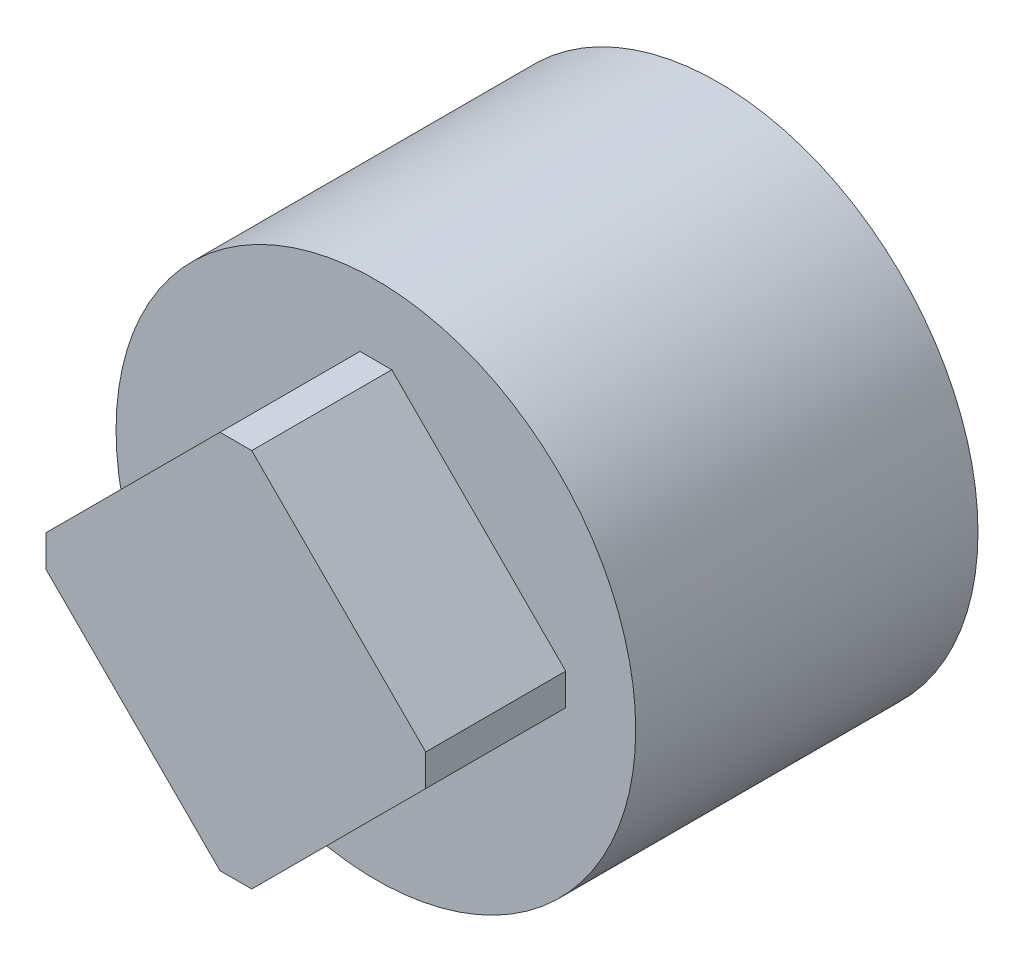
SolidWorks part; units mm, degrees
ref_plane "Front Plane" through (0, 0, 0) normal (0, 0, 1) x (1, 0, 0)
ref_plane "Top Plane" through (0, 0, 0) normal (0, 1, 0) x (1, 0, 0)
ref_plane "Right Plane" through (0, 0, 0) normal (1, 0, 0) x (0, 0, -1)
sketch "Sketch1" plane through (0, 0, 0) normal (0, 0, 1) x (1, 0, 0)
  circle A0 centre (0, 0) radius 16.7
extrude "Replaceable drive insert body" add sketch "Sketch1" along normal blind 22 from offset 1
sketch "Sketch2" plane through (0, 0, 0) normal (0, 0, 1) x (1, 0, 0)
  line L0 (1.02, 12.2029) -> (-1.02, 12.2029)
  line L1 (-1.02, 12.2029) -> (-12.2029, 1.02)
  line L2 (-12.2029, 1.02) -> (-12.2029, -1.02)
  line L3 (-12.2029, -1.02) -> (-1.02, -12.2029)
  line L4 (-1.02, -12.2029) -> (1.02, -12.2029)
  line L5 (1.02, -12.2029) -> (12.2029, -1.02)
  line L6 (12.2029, -1.02) -> (12.2029, 1.02)
  line L7 (12.2029, 1.02) -> (1.02, 12.2029)
extrude "Common positive drive tang" add sketch "Sketch2" along normal blind 9 from offset 23
sketch "Sketch3" plane through (0, 0, 0) normal (0, 0, 1) x (1, 0, 0)
  line L0 (1.02, 6.8996) -> (-1.02, 6.8996)
  line L1 (-1.02, 6.8996) -> (-6.8996, 1.02)
  line L2 (-6.8996, 1.02) -> (-6.8996, -1.02)
  line L3 (-6.8996, -1.02) -> (-1.02, -6.8996)
  line L4 (-1.02, -6.8996) -> (1.02, -6.8996)
  line L5 (1.02, -6.8996) -> (6.8996, -1.02)
  line L6 (6.8996, -1.02) -> (6.8996, 1.02)
  line L7 (6.8996, 1.02) -> (1.02, 6.8996)
extrude "Valve stem socket, nominal flats 11 mm" cut sketch "Sketch3" along normal blind 19.1 from offset 1
sketch "Sketch4" plane through (0, 0, 0) normal (0, 0, 1) x (1, 0, 0)
  circle A0 centre (0, 0) radius 10.2
extrude "Stem corner clearance at entry" cut sketch "Sketch4" along normal blind 1.1 from offset 1
